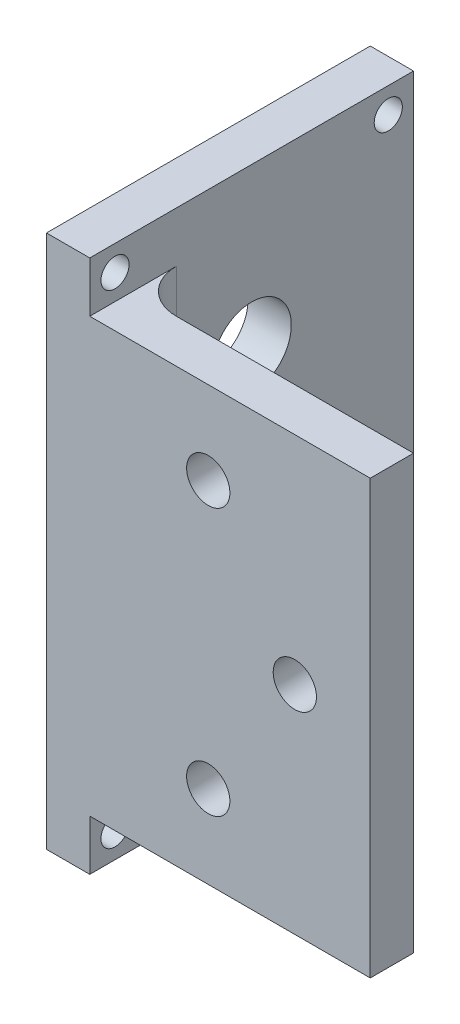
SolidWorks part; units mm, degrees
ref_plane "Front Plane" through (0, 0, 0) normal (0, 0, 1) x (1, 0, 0)
ref_plane "Top Plane" through (0, 0, 0) normal (0, 1, 0) x (1, 0, 0)
ref_plane "Right Plane" through (0, 0, 0) normal (1, 0, 0) x (0, 0, -1)
sketch "Sketch1" plane through (0, 0, 0) normal (0, 1, 0) x (1, 0, 0)
  line L0 (0, 0) -> (22.44, 0)
  line L1 (22.44, 0) -> (22.44, 3)
  line L2 (22.44, 3) -> (3, 3)
  line L3 (3, 3) -> (3, 22.44)
  line L4 (3, 22.44) -> (0, 22.44)
  line L5 (0, 22.44) -> (0, 0)
  dimension "D1" = 22.44
  dimension "D2" = 22.44
  dimension "D3" = 3
  dimension "D4" = 3
extrude "Boss-Extrude1" add sketch "Sketch1" along normal blind 37 contours L3 L4 L5 L0 L1 L2
fillet "Fillet1" radius 3 1 edges at (3, 18.5, -3)
sketch "Sketch2" plane through (0, 0, -22.44) normal (0, 0, -1) x (-1, 0, 0)
  line L0 (-22.44, 37) -> (-22.44, 0) construction
  line L1 (-3, 0) -> (-22.44, 0)
  line L2 (-3, 0) -> (-3, 3.5)
  line L3 (-3, 3.5) -> (-22.44, 3.5)
  line L4 (-22.44, 0) -> (-22.44, 3.5)
  line L6 (-3, 37) -> (-22.44, 37)
  line L7 (-3, 37) -> (-3, 33.5)
  line L8 (-3, 33.5) -> (-22.44, 33.5)
  line L9 (-22.44, 37) -> (-22.44, 33.5)
  circle A0 centre (-11.2128, 27.75) radius 1.5
  circle A1 centre (-17.2128, 18.5) radius 1.5
  circle A2 centre (-11.2128, 9.25) radius 1.5
  dimension "D8" = 3
  dimension "D1" = 3.5
  dimension "D2" = 3.5
  dimension "D3" = 18.5
  dimension "D4" = 9.25
  dimension "D5" = 9.25
  dimension "D6" = 9.25
  dimension "D7" = 6
extrude "Cut-Extrude1" cut sketch "Sketch2" against normal through all
sketch "Sketch3" plane through (0, 0, 0) normal (-1, 0, 0) x (0, 0, 1)
  line L0 (-22.44, 37) -> (0, 37) construction
  line L1 (-22.44, 37) -> (-22.44, 0) construction
  line L2 (-22.44, 0) -> (0, 0) construction
  line L3 (0, 37) -> (0, 0) construction
  circle A0 centre (-1.75, 35.25) radius 0.975
  circle A1 centre (-1.75, 1.75) radius 0.975
  circle A2 centre (-20.69, 1.75) radius 0.975
  circle A3 centre (-20.69, 35.25) radius 0.975
  circle A4 centre (-11.22, 26) radius 2.75
  dimension "D1" = 1.95
  dimension "D6" = 5.5
  dimension "D2" = 1.75
  dimension "D3" = 1.75
  dimension "D4" = 1.75
  dimension "D5" = 1.75
  dimension "D7" = 11.22
  dimension "D8" = 11.22
  dimension "D9" = 11
extrude "Cut-Extrude2" cut sketch "Sketch3" against normal through all
